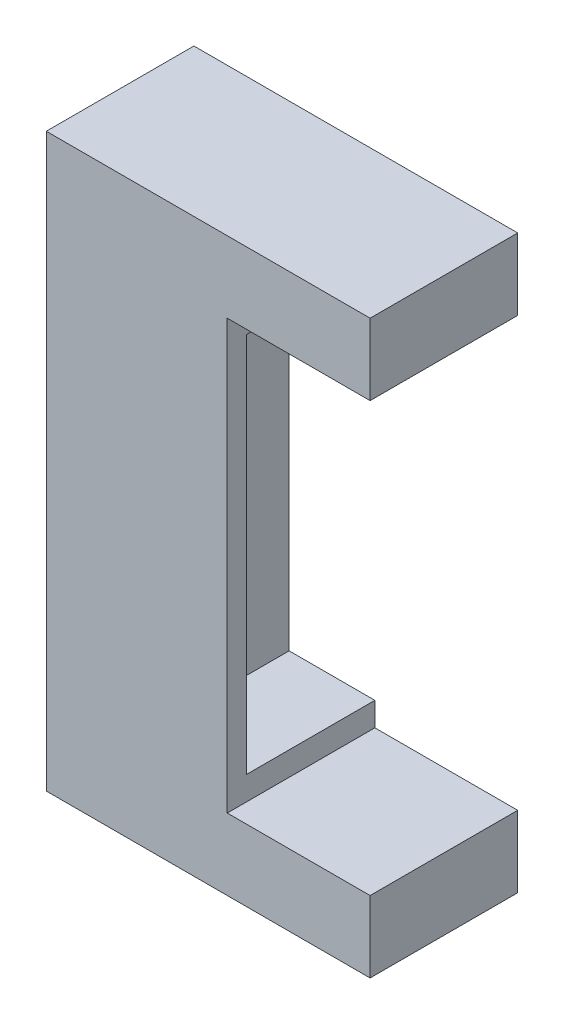
SolidWorks part; units mm, degrees
ref_plane "Front Plane" through (0, 0, 0) normal (0, 0, 1) x (1, 0, 0)
ref_plane "Top Plane" through (0, 0, 0) normal (0, 1, 0) x (1, 0, 0)
ref_plane "Right Plane" through (0, 0, 0) normal (1, 0, 0) x (0, 0, -1)
sketch "Sketch1" plane through (0, 0, 0) normal (0, 0, 1) x (1, 0, 0)
  line L0 (-24.5, 6) -> (-17.7, 6)
  line L1 (-22.5, 4) -> (-19.7, 4)
  line L2 (-22.5, 4) -> (-22.5, -4)
  line L3 (-22.5, -4) -> (-19.7, -4)
  line L4 (-19.7, 4) -> (-19.7, -4)
  line L5 (-17.7, 6) -> (-17.7, -6)
  line L6 (-24.5, -6) -> (-17.7, -6)
  line L7 (-24.5, 6) -> (-24.5, -6)
  dimension "D1" = 2
extrude "Boss-Extrude2" add sketch "Sketch1" along normal blind 2.7
sketch "Sketch2" plane through (0, 0, 2.7) normal (0, 0, 1) x (1, 0, 0)
  line L1 (-24.5, 6) -> (-17.7, 6)
  line L2 (-24.5, 6) -> (-24.5, -6)
  line L3 (-24.5, -6) -> (-17.7, -6)
  line L4 (-17.7, 6) -> (-17.7, -6)
extrude "Boss-Extrude3" add sketch "Sketch2" along normal blind 0.4
sketch "Sketch3" plane through (0, 0, 3.1) normal (0, 0, 1) x (1, 0, 0)
  line L0 (-17.7, -6) -> (-17.7, 6) construction
  line L1 (-17.7, 4.5) -> (-20.7, 4.5)
  line L2 (-17.7, 4.5) -> (-17.7, -4.5)
  line L3 (-17.7, -4.5) -> (-20.7, -4.5)
  line L4 (-20.7, 4.5) -> (-20.7, -4.5)
  dimension "D1" = 1.5
  dimension "D2" = 1.5
  dimension "D3" = 3
extrude "Cut-Extrude1" cut sketch "Sketch3" against normal through all
